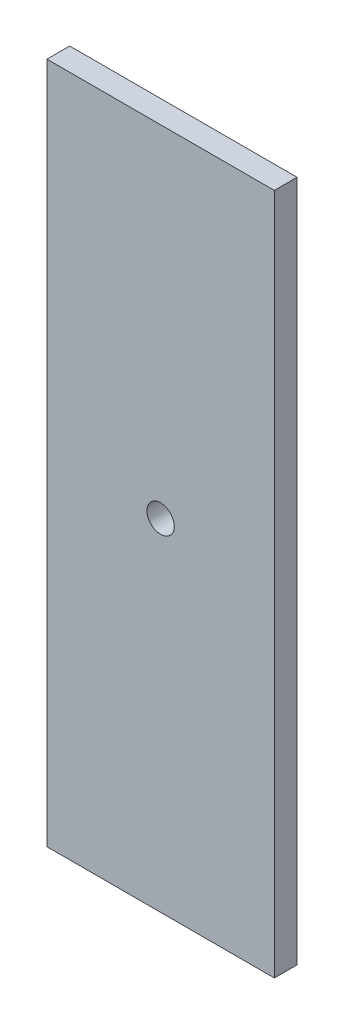
SolidWorks part; units mm, degrees
ref_plane "Front Plane" through (0, 0, 0) normal (0, 0, 1) x (1, 0, 0)
ref_plane "Top Plane" through (0, 0, 0) normal (0, 1, 0) x (1, 0, 0)
ref_plane "Right Plane" through (0, 0, 0) normal (1, 0, 0) x (0, 0, -1)
sketch "Sketch1" plane through (0, 0, 0) normal (0, 0, 1) x (1, 0, 0)
  line L1 (-25, -75) -> (25, -75)
  line L2 (-25, -75) -> (-25, 75)
  line L3 (-25, 75) -> (25, 75)
  line L4 (25, -75) -> (25, 75)
  line L5 (-25, -75) -> (25, 75) construction
  line L6 (-25, 75) -> (25, -75) construction
  point P0 (0, 0)
  dimension "D1" = 150
  dimension "D2" = 50
extrude "Boss-Extrude1" add sketch "Sketch1" along normal blind 5
sketch "Sketch2" plane through (0, 0, 5) normal (0, 0, 1) x (1, 0, 0)
  circle A0 centre (0, 0) radius 3
  dimension "D1" = 6
extrude "Cut-Extrude1" cut sketch "Sketch2" against normal through all
